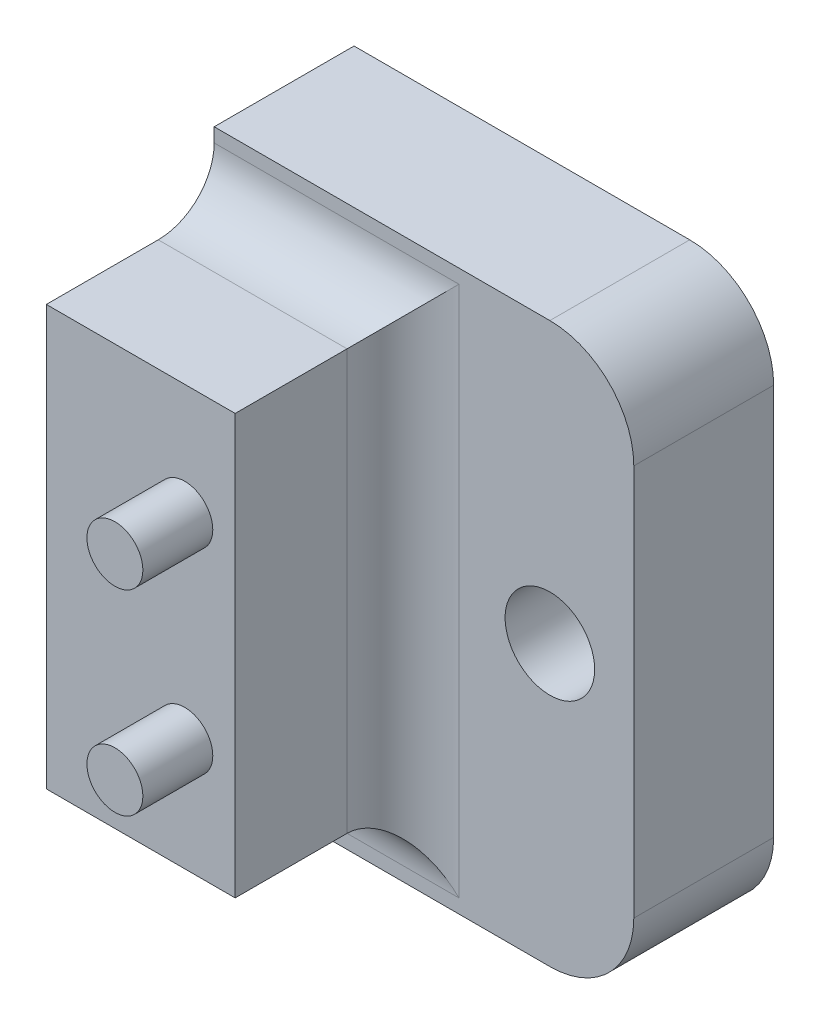
SolidWorks part; units mm, degrees
ref_plane "Alzado" through (0, 0, 0) normal (0, 0, 1) x (1, 0, 0)
ref_plane "Planta" through (0, 0, 0) normal (0, 1, 0) x (1, 0, 0)
ref_plane "Vista lateral" through (0, 0, 0) normal (1, 0, 0) x (0, 0, -1)
sketch "Croquis1" plane through (0, 0, 0) normal (0, 0, 1) x (1, 0, 0)
  line L1 (0, 0) -> (12, 0)
  line L2 (0, 0) -> (0, 20)
  line L3 (0, 20) -> (12, 20)
  line L4 (15, 3) -> (15, 17)
  circle A0 centre (12, 10) radius 1.6
  arc A1 (12, 20) -> (15, 17) centre (12, 17) cw
  arc A2 (12, 0) -> (15, 3) centre (12, 3) ccw
  point P9 (15, 20)
  dimension "D3" = 3.2
  dimension "D5" = 3
  dimension "D1" = 20
  dimension "D2" = 15
  dimension "D4" = 3
extrude "Saliente-Extruir1" add sketch "Croquis1" along normal blind 5
sketch "Croquis2" plane through (0, 0, 5) normal (0, 0, 1) x (1, 0, 0)
  line L0 (0, 20) -> (0, 0) construction
  line L1 (0, 17.5) -> (6.75, 17.5)
  line L2 (0, 17.5) -> (0, 2.5)
  line L3 (0, 2.5) -> (6.75, 2.5)
  line L4 (6.75, 17.5) -> (6.75, 2.5)
  line L5 (12, 20) -> (0, 20) construction
  dimension "D1" = 6.75
  dimension "D2" = 15
  dimension "D3" = 2.5
extrude "Saliente-Extruir2" add sketch "Croquis2" along normal blind 6
fillet "Redondeo1" radius 2 3 edges at (3.375, 17.5, 5) (6.75, 10, 5) (3.375, 2.5, 5)
sketch "Croquis3" plane through (0, 0, 11) normal (0, 0, 1) x (1, 0, 0)
  line L1 (0, 2.5) -> (6.75, 2.5) construction
  circle A0 centre (4.9502, 13.5) radius 1
  circle A1 centre (4.9502, 6.5) radius 1
  point P6 (0, 0)
  dimension "D1" = 2
  dimension "D2" = 2
  dimension "D3" = 7
  dimension "D4" = 4
extrude "Saliente-Extruir3" add sketch "Croquis3" along normal blind 2.5
